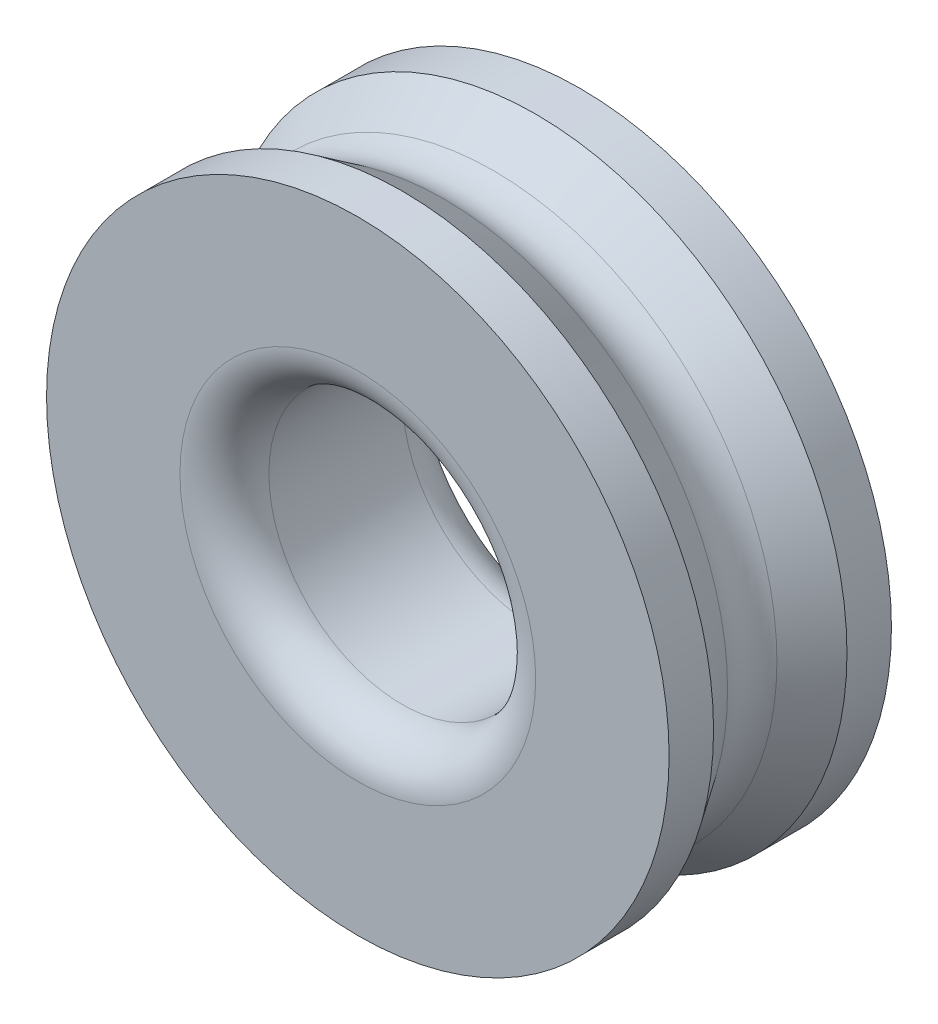
SolidWorks part; units mm, degrees
ref_plane "Спереди" through (0, 0, 0) normal (0, 0, 1) x (1, 0, 0)
ref_plane "Сверху" through (0, 0, 0) normal (0, 1, 0) x (1, 0, 0)
ref_plane "Справа" through (0, 0, 0) normal (1, 0, 0) x (0, 0, -1)
sketch "Эскиз2" plane through (0, 0, 0) normal (0, 1, 0) x (1, 0, 0)
  line L0 (7, 0) -> (0, 0)
  line L1 (0, 0) -> (0, 3)
  line L2 (0, 3) -> (7, 3)
  line L3 (7, 3) -> (6, 1.5)
  line L4 (6, 1.5) -> (7, 0)
  line L5 (0, 1.5) -> (6, 1.5) construction
  dimension "D2" = 1
  dimension "D1" = 3
  dimension "D3" = 7
revolve "Повернуть1" add sketch "Эскиз2" angle 360 about L1
sketch "Эскиз3" plane through (0, 0, -3) normal (0, 0, -1) x (-1, 0, 0)
  circle A0 centre (0, 0) radius 7
  dimension "D1" = 14
extrude "Вытянуть1" add sketch "Эскиз3" along normal blind 1
sketch "Эскиз4" plane through (0, 0, 0) normal (0, 0, 1) x (1, 0, 0)
  circle A0 centre (0, 0) radius 7
  circle A2 centre (0, 0) radius 7 construction
extrude "Вытянуть2" add sketch "Эскиз4" along normal blind 1
sketch "Эскиз5" plane through (0, 0, -4) normal (0, 0, -1) x (-1, 0, 0)
  circle A0 centre (0, 0) radius 3
  dimension "D1" = 6
extrude "Вытянуть3" cut sketch "Эскиз5" against normal through all
fillet "Скругление2" radius 1 1 edges at (6, 0, -1.5)
fillet "Скругление3" radius 1 2 edges at (-3, 0, -4) (-3, 0, 1)
